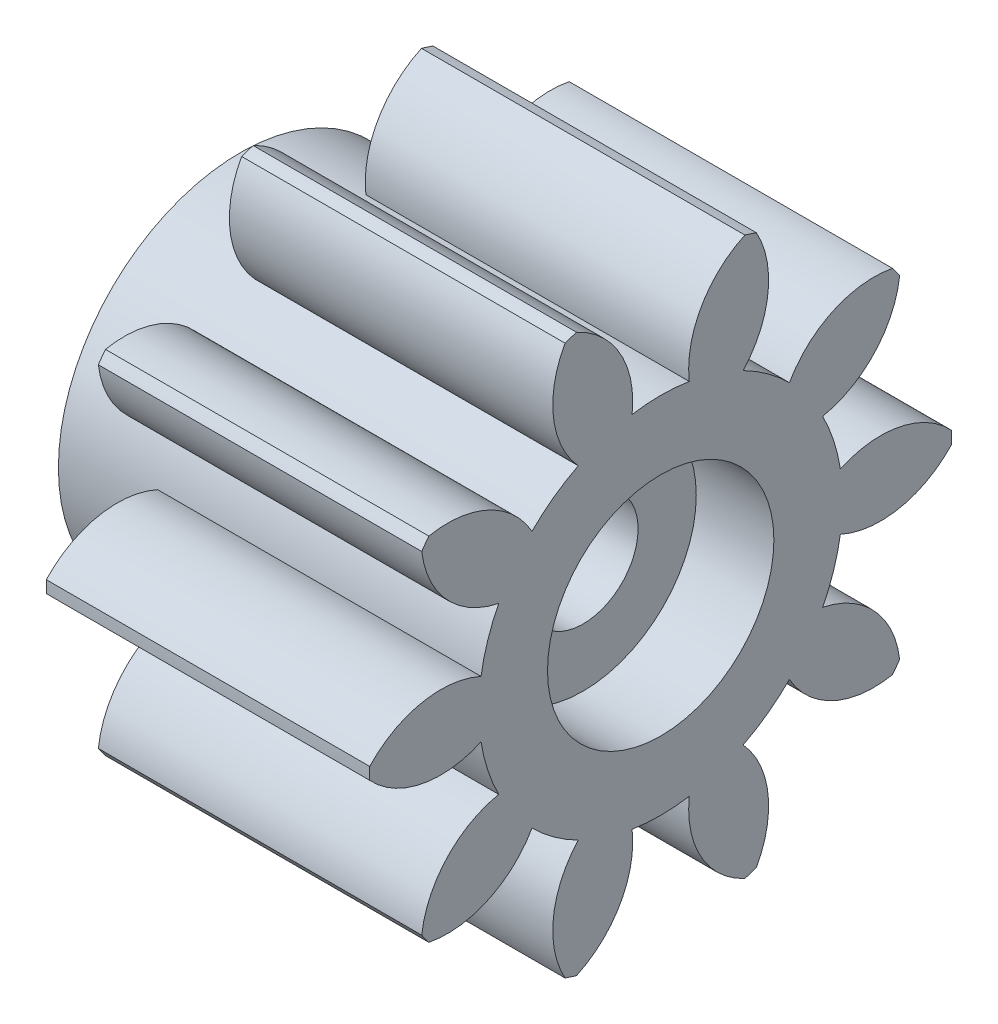
SolidWorks part; units mm, degrees
material "7075-O (SS)"
ref_plane "Plane1" through (0, 0, 0) normal (0, 0, 1) x (1, 0, 0)
ref_plane "Plane2" through (0, 0, 0) normal (0, 1, 0) x (1, 0, 0)
ref_plane "Plane3" through (0, 0, 0) normal (1, 0, 0) x (0, 0, -1)
sketch "HoldingSke" plane through (0, 0, 0) normal (0, 1, 0) x (1, 0, 0)
  line L0 (0, 0) -> (0.6565, -0.1158)
  line L1 (-15, 0) -> (100, 0) construction
  line L2 (0, 0) -> (-2.1039, 2.3779)
  line L3 (0, 0) -> (-11.863, 4.5341)
  line L4 (0, 0) -> (8.5048, 1.4996)
  line L5 (0, 0) -> (-46.8476, -17.4728)
  line L6 (0, 0) -> (-8.2896, -5.593)
  line L7 (-2.1039, 2.3779) -> (8.6589, 51.2072)
  line L8 (-76.2, 54.61) -> (-76.1, 54.61)
  line L9 (-71.009, 38.7566) -> (-53.1078, 45.2721)
  line L10 (-76.2, 71.12) -> (104.1128, 71.12)
  line L11 (0, 0) -> (-10, 0)
  line L12 (-76.2, 101.6) -> (-76.147, 101.6)
  line L13 (24.9733, 27.94) -> (52.9518, 28.4284)
  line L14 (24.9733, 27.94) -> (24.9743, 27.94)
  line L15 (24.9733, 27.94) -> (100.4006, 29.5858)
  line L16 (-63.627, -1.5) -> (-12.827, -1.5)
  circle A0 centre (0, 0) radius 0.4
  circle A1 centre (0, 0) radius 5.624
  circle A2 centre (0, 0) radius 37.5
  circle A3 centre (0, 0) radius 0.4
  dimension "MHD" = 11.248
  dimension "Hub_dia" = 75
  dimension "Bore" = 0.8
  dimension "MBD" = 0.8
  dimension "Num_teeth" = 10
  dimension "Pitch" = 0.6667
  dimension "Overall_len" = 50
  dimension "Show_teeth" = 10
  dimension "Thickness" = 10
  dimension "OAL" = 50.0014
  dimension "T_dim" = 0.1
  dimension "Ap" = 20
  dimension "H" = 19.05
  dimension "Pitch_radius" = 180.3128
  dimension "Width" = 10
  dimension "Backlash" = 0.053
  dimension "Addendum_fac" = 1
  dimension "Dedendum_fac" = 1.25
  dimension "Clearance_fac" = 0.25
  dimension "Dedendum_add" = 0.001
  dimension "Module" = 1.5
sketch "BasProSke" plane through (0, 0, 0) normal (0, 1, 0) x (1, 0, 0)
  line L0 (-10, 0) -> (60, 0) construction
  line L1 (0, 0) -> (0, 9)
  line L2 (0, 0) -> (10, 0)
  line L3 (10, 0) -> (10, 9)
  line L4 (10, 9) -> (0, 9)
  dimension "Thickness" = 10
  dimension "Diameter" = 18
revolve "Base-Revolve" add sketch "BasProSke" angle 360 about L0
sketch "TooCutSke" plane through (0, 0, 0) normal (1, 0, 0) x (0, 0, -1)
  line L1 (0, 0) -> (0, 107) construction
  line L2 (0, 0) -> (-1.2658, 7.3924) construction
  line L3 (0, 0) -> (-4.5869, 14.117) construction
  line L4 (-1.2658, 7.3924) -> (-2.2934, 7.0585) construction
  arc A0 (0.8839, 5.5541) -> (-0.8839, 5.5541) centre (0, 0) ccw
  arc A1 (2.6378, 8.6313) -> (-2.6378, 8.6313) centre (0, 0) ccw
  circle A2 centre (0, 0) radius 7.5 construction
  circle A3 centre (0, 0) radius 7.0477 construction
  arc A4 (-0.8839, 5.5541) -> (-2.6378, 8.6313) centre (-3.8646, 5.8936) ccw
  arc A5 (2.6378, 8.6313) -> (0.8839, 5.5541) centre (3.8646, 5.8936) ccw
  dimension "Root_dia" = 11.248
  dimension "Overcut_dia" = 18.0508
  dimension "Pitch_dia" = 15
  dimension "Base_dia" = 14.0954
  dimension "Flank_rad" = 3
  dimension "Half_ang" = 18
  dimension "Half_CT" = 1.0805
extrude "ToothCut" cut sketch "TooCutSke" along normal through all
fillet "Breaks" [suppressed] radius 0.03
fillet "RootFillets" [suppressed] radius 0.376
pattern_circular "TeethCuts" count 10 over 360 about axis through (0, 0, 0) along (1, 0, 0) of "ToothCut", "RootFillets", "Breaks"
sketch "HubNeaOneSke" plane through (0, 0, 0) normal (-1, 0, 0) x (0, 0, 1)
  circle A0 centre (0, 0) radius 5.624
  dimension "Diameter" = 11.248
extrude "HubNearOne" [suppressed] add sketch "HubNeaOneSke" along normal blind 40.0014
sketch "HubNeaBotSke" plane through (0, 0, 0) normal (-1, 0, 0) x (0, 0, 1)
  circle A0 centre (0, 0) radius 5.624
  dimension "Diameter" = 11.248
extrude "HubNearBoth" [suppressed] add sketch "HubNeaBotSke" along normal blind 20.0007
ref_plane "FarPln" through (10, 0, 0) normal (1, 0, 0) x (0, 0, -1)
sketch "HubFarSke" plane through (10, 0, 0) normal (1, 0, 0) x (0, 0, -1)
  circle A0 centre (0, 0) radius 5.624
  dimension "Diameter" = 11.248
extrude "HubFar" [suppressed] add sketch "HubFarSke" along normal blind 20.0007
sketch "KeySke" plane through (0, 0, 0) normal (1, 0, 0) x (0, 0, -1)
  line L0 (-0.05, 0) -> (-0.05, 0.5)
  line L1 (-0.05, 0.5) -> (0.05, 0.5)
  line L2 (0.05, 0.5) -> (0.05, 0)
  line L3 (0, 0) -> (0, 34) construction
  line L4 (-0.05, 0) -> (0.05, 0)
  dimension "Offset" = 0.5
  dimension "Width" = 0.1
extrude "Keyway" [suppressed] cut sketch "KeySke" along normal mid plane 100.0027
pattern_circular "Keyway2" [suppressed] count 2 every 90 about axis through (-10, 0, 0) along (1, 0, 0)
sketch "Croquis2" plane through (0, 0, 0) normal (-1, 0, 0) x (0, 0, 1)
  circle A0 centre (0, 0) radius 5.624
  arc A1 (5.5554, 0.8757) -> (5.0091, 2.5569) centre (0, 0) ccw construction
extrude "Saliente-Extruir2" add sketch "Croquis2" along normal blind 3
hole_wizard "Refrentado para tornillo con cabeza troncocónica de M31" positions "Croquis3" profile "Croquis4" counterbore size "M3" standard "Ansi Metric" end condition up to next
sketch "Croquis3" plane through (10, 0, 0) normal (1, 0, 0) x (0, 0, -1)
  point P0 (0, 0)
sketch "Croquis4" plane through (10, 0, 0) normal (0, 1, 0) x (0, 0, -1)
  line L0 (0, 0) -> (0, 13)
  line L1 (0, 13) -> (1.7, 13)
  line L3 (1.7, 13) -> (1.7, 2.4)
  line L4 (1.7, 2.4) -> (3.5, 2.4)
  line L5 (3.5, 2.4) -> (3.5, 0)
  line L7 (3.5, 0) -> (0, 0)
  line L11 (0, -6.35) -> (0, 107.95) construction
  dimension "Diámetro de taladro hasta el siguiente" = 3.4
  dimension "Profundidad de taladro hasta el siguiente" = 13
  dimension "Diámetro de refrentado" = 7
  dimension "Profundidad de refrentado" = 2.4
sketch "Croquis5" plane through (-3, 0, 0) normal (-1, 0, 0) x (0, 0, 1)
  line L0 (0, 0) -> (0, 3.6) construction
  circle A0 centre (0, 3.6) radius 1
  circle A3 centre (3.1177, -1.8) radius 1
  circle A4 centre (-3.1177, -1.8) radius 1
  circle A6 centre (0, 0) radius 1.7 construction
  dimension "D1" = 2
  dimension "D3" = 3.6
  dimension "D2" = 3
extrude "Cortar-Extruir1" cut sketch "Croquis5" against normal blind 3
equation "' \"Module@HoldingSke\" = 6.35"
equation "' \"Num_teeth@HoldingSke\" = 12"
equation "' \"Ap@HoldingSke\" =  20"
equation "' \"Ap@HoldingSke\" = 20"
equation "' \"Width@HoldingSke\" = 0.5 * 25.4"
equation "' \"Hub_dia@HoldingSke\"= 1 * 25.4"
equation "' \"Hub_dia@HoldingSke\" = 1 * 25.4"
equation "' \"Overall_len@HoldingSke\" = 1.0 * 25.4"
equation "' \"Bore@HoldingSke\" = 0.75 * 25.4"
equation "' \"T_dim@HoldingSke\" = 0.1 * 25.4"
equation "' \"Width@KeySke\" = 0.25 * 25.4"
equation "' \"Show_teeth@HoldingSke\" = 13"
equation "' \"Backlash@HoldingSke\" = 0.009 * 25.4"
equation "' \"Addendum_fac@HoldingSke\" = 1.0"
equation "' \"Dedendum_fac@HoldingSke\" = 1.25"
equation "' \"Dedendum_add@HoldingSke\" = 0.00005 * 25.4"
equation "' \"Clearance_fac@HoldingSke\" = 0.25"
equation "\"Pitch@HoldingSke\" = 1 / \"Module@HoldingSke\""
equation "\"Overcut_dia@TooCutSke\" = (\"Num_teeth@HoldingSke\" + 2 * \"Addendum_fac@HoldingSke\") / \"Pitch@HoldingSke\" + 0.002 * 25.4"
equation "\"Pitch_dia@TooCutSke\" = \"Num_teeth@HoldingSke\" / \"Pitch@HoldingSke\""
equation "\"Base_dia@TooCutSke\" = \"Num_teeth@HoldingSke\" / \"Pitch@HoldingSke\" * cos((\"Ap@HoldingSke\"  * 3.14159265 / 180))"
equation "\"Root_dia@TooCutSke\" = (\"Num_teeth@HoldingSke\" + 2) / \"Pitch@HoldingSke\" - 2 * (\"Addendum_fac@HoldingSke\" + \"Dedendum_fac@HoldingSke\") / \"Pitch@HoldingSke\" - \"Dedendum_add@HoldingSke\" * 2"
equation "\"Half_ang@TooCutSke\" = 180 / \"Num_teeth@HoldingSke\""
equation "\"Half_CT@TooCutSke\" = \"Num_teeth@HoldingSke\" / \"Pitch@HoldingSke\" * sin((3.14159265 / 2 / \"Num_teeth@HoldingSke\")) / 2 - 7 * \"Backlash@HoldingSke\" / 4"
equation "\"Flank_rad@TooCutSke\" = \"Num_teeth@HoldingSke\" / \"Pitch@HoldingSke\" / 5"
equation "\"Radius@RootFillets\" = \"Clearance_fac@HoldingSke\" / \"Pitch@HoldingSke\" + \"Dedendum_add@HoldingSke\""
equation "\"Break_rad@Breaks\" = 0.02 / \"Pitch@HoldingSke\""
equation "\"Thickness@HoldingSke\" = \"Width@HoldingSke\""
equation "\"OAL@HoldingSke\" = \"Thickness@HoldingSke\""
equation "\"MHD@HoldingSke\" = (\"Num_teeth@HoldingSke\" + 2) / \"Pitch@HoldingSke\" - 2 * (\"Addendum_fac@HoldingSke\" + \"Dedendum_fac@HoldingSke\")  / \"Pitch@HoldingSke\" - \"Dedendum_add@HoldingSke\" * 2"
equation "\"MBD@HoldingSke\" = (\"Num_teeth@HoldingSke\" + 2) / \"Pitch@HoldingSke\" - 2 * (\"Addendum_fac@HoldingSke\" + \"Dedendum_fac@HoldingSke\")  / \"Pitch@HoldingSke\" - \"Dedendum_add@HoldingSke\" * 2 - 0.002 * 25.4"
equation "\"MHD@HoldingSke\" = ((sgn( \"MHD@HoldingSke\" - \"Hub_dia@HoldingSke\" )-1)*( \"MHD@HoldingSke\" - \"Hub_dia@HoldingSke\" ))/-2+ \"Hub_dia@HoldingSke\""
equation "\"MBD@HoldingSke\" = ((sgn( \"MBD@HoldingSke\" - \"Bore@HoldingSke\" )-1)*( \"MBD@HoldingSke\" - \"Bore@HoldingSke\" ))/-2+ \"Bore@HoldingSke\""
equation "\"OAL@HoldingSke\" = ((sgn( \"OAL@HoldingSke\" - \"Overall_len@HoldingSke\" )+1)*( \"OAL@HoldingSke\" - \"Overall_len@HoldingSke\" ))/2 + \"Overall_len@HoldingSke\" + 0.000002 * 25.4"
equation "\"Num_teeth@TeethCuts\" = int( \"Show_teeth@HoldingSke\" ) + 1"
equation "\"Num_teeth@TeethCuts\" = ((sgn( \"Num_teeth@TeethCuts\" - \"Num_teeth@HoldingSke\" )-1)*( \"Num_teeth@TeethCuts\" - \"Num_teeth@HoldingSke\" ))/-2+ \"Num_teeth@HoldingSke\""
equation "\"Num_teeth@TeethCuts\" = ((sgn( \"Num_teeth@TeethCuts\" - 2.0)+1)*( \"Num_teeth@TeethCuts\" - 2.0))/2 +2.0"
equation "\"Angle@TeethCuts\" = 360.0 / \"Num_teeth@HoldingSke\""
equation "\"Diameter@BasProSke\" = (\"Num_teeth@HoldingSke\" + 2 * \"Addendum_fac@HoldingSke\") / \"Pitch@HoldingSke\""
equation "\"Thickness@BasProSke\"  = \"Thickness@HoldingSke\""
equation "' \"Fillet_rad@BasProSke\" =  \"Thickness@HoldingSke\" * 0.05"
equation "' \"Fillet_rad@BasProSke\" = \"Thickness@HoldingSke\" * 0.05"
equation "\"MHD@HoldingSke\" = ((sgn( \"MHD@HoldingSke\" - \"Root_dia@TooCutSke\" )-1)*( \"MHD@HoldingSke\" - \"Root_dia@TooCutSke\" ))/-2+ \"Root_dia@TooCutSke\""
equation "\"Diameter@HubNeaOneSke\" = \"MHD@HoldingSke\""
equation "\"Length@HubNearOne\" = \"OAL@HoldingSke\" - \"Thickness@BasProSke\""
equation "\"Diameter@HubNeaBotSke\" = \"MHD@HoldingSke\""
equation "\"Length@HubNearBoth\" = ( \"OAL@HoldingSke\" - \"Thickness@BasProSke\" ) / 2.0"
equation "\"Thickness@FarPln\" = \"Thickness@BasProSke\""
equation "\"Diameter@HubFarSke\" = \"MHD@HoldingSke\""
equation "\"Length@HubFar\" = ( \"OAL@HoldingSke\" - \"Thickness@BasProSke\" ) / 2.0"
equation "\"Diameter@BorSke\" = \"MBD@HoldingSke\""
equation "\"D1@Bore\" = \"OAL@HoldingSke\" * 2.0"
equation "\"D1@Keyway\" = \"OAL@HoldingSke\" * 2.0"
equation "\"Offset@KeySke\" = \"T_dim@HoldingSke\" + \"MBD@HoldingSke\" / 2.0"
